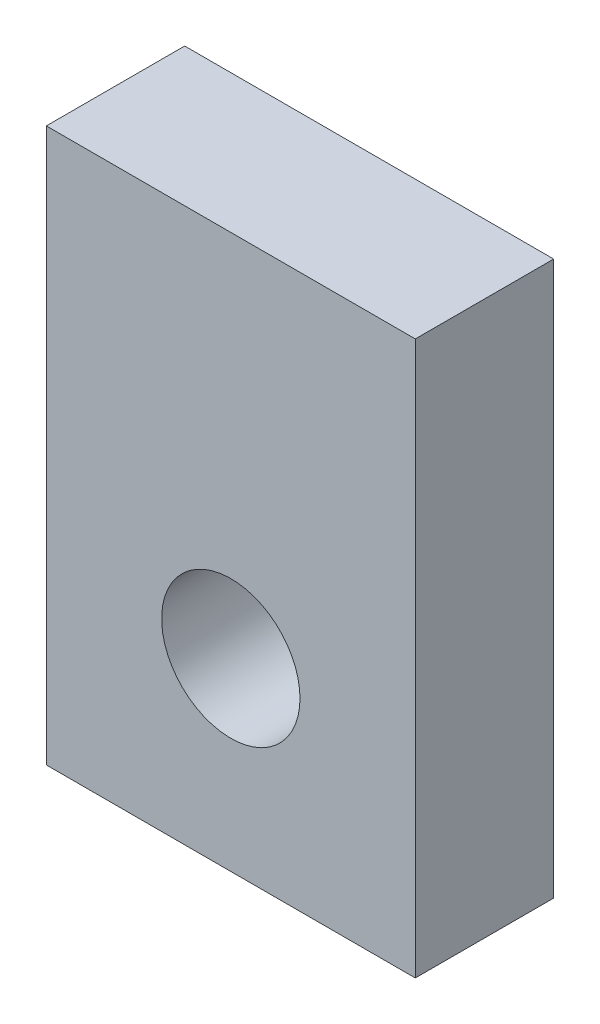
SolidWorks part; units mm, degrees
ref_plane "Спереди" through (0, 0, 0) normal (0, 0, 1) x (1, 0, 0)
ref_plane "Сверху" through (0, 0, 0) normal (0, 1, 0) x (1, 0, 0)
ref_plane "Справа" through (0, 0, 0) normal (1, 0, 0) x (0, 0, -1)
other "Configuration Table"
sketch "Эскиз1" plane through (0, 0, 0) normal (0, 0, 1) x (1, 0, 0)
  line L0 (4, 12) -> (4, 0) construction
  line L1 (0, 0) -> (8, 0)
  line L2 (0, 0) -> (0, 12)
  line L3 (0, 12) -> (8, 12)
  line L4 (8, 0) -> (8, 12)
  line L5 (0, 6) -> (8, 6) construction
  dimension "D1" = 8
  dimension "D2" = 12
extrude "Бобышка-Вытянуть1" add sketch "Эскиз1" along normal blind 3
sketch "Эскиз2" plane through (0, 0, 3) normal (0, 0, 1) x (1, 0, 0)
  line L0 (0, 0) -> (8, 0) construction
  line L7 (0, 12) -> (0, 0) construction
  circle A0 centre (4, 4) radius 1.5
  dimension "D1" = 3
  dimension "D2" = 4
  dimension "D3" = 4
extrude "Вырез-Вытянуть1" cut sketch "Эскиз2" against normal through all
